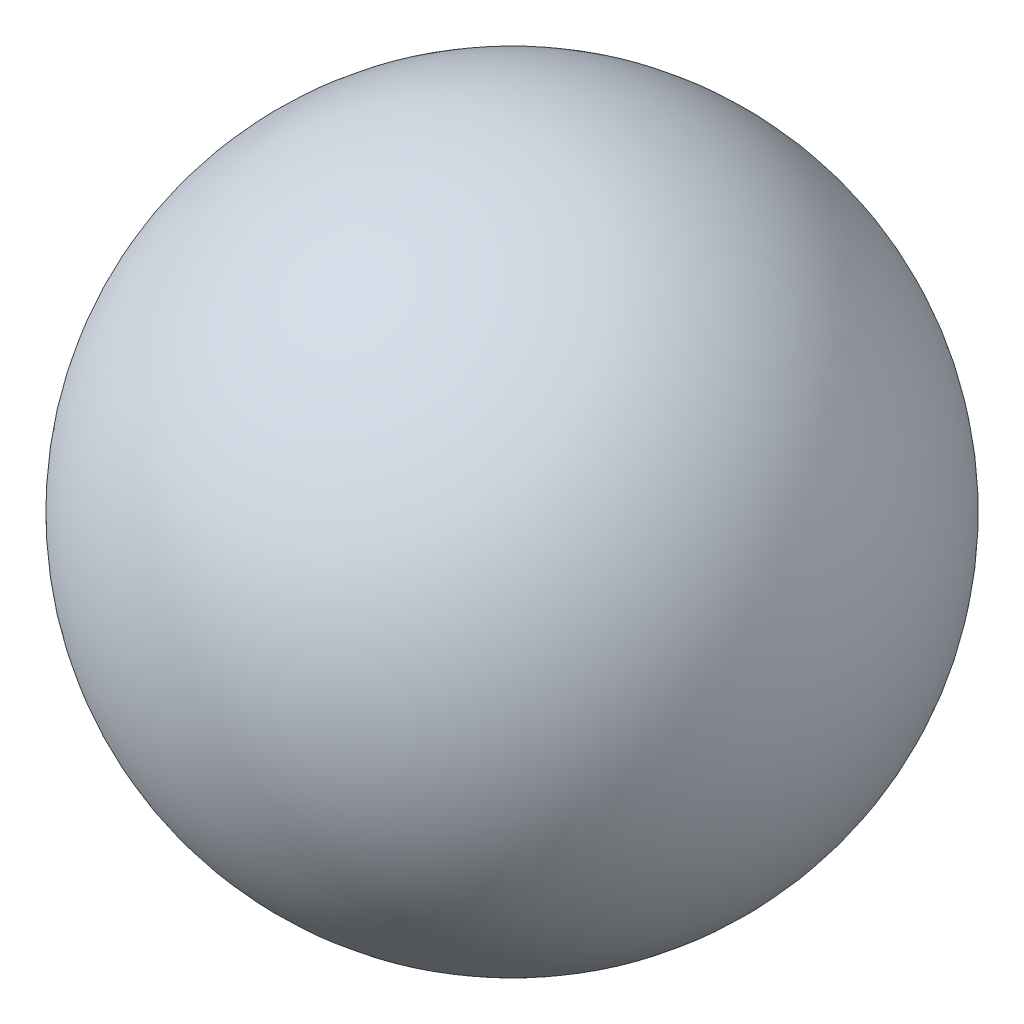
SolidWorks part; units mm, degrees
ref_plane "Front Plane" through (0, 0, 0) normal (0, 0, 1) x (1, 0, 0)
ref_plane "Top Plane" through (0, 0, 0) normal (0, 1, 0) x (1, 0, 0)
ref_plane "Right Plane" through (0, 0, 0) normal (1, 0, 0) x (0, 0, -1)
sketch "Sketch1" plane through (0, 0, 0) normal (0, 0, 1) x (1, 0, 0)
  line L0 (0, 4) -> (0, -4)
  arc A0 (0, -4) -> (0, 4) centre (0, 0) ccw
  dimension "D1" = 8
revolve "Revolve1" add sketch "Sketch1" angle 360 about L0
